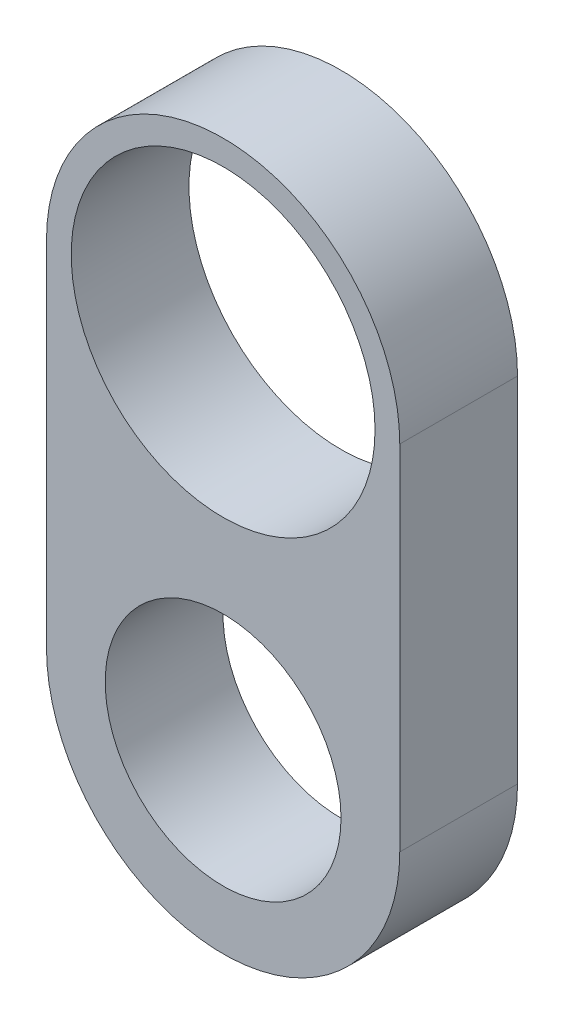
SolidWorks part; units mm, degrees
ref_plane "Front Plane" through (0, 0, 0) normal (0, 0, 1) x (1, 0, 0)
ref_plane "Top Plane" through (0, 0, 0) normal (0, 1, 0) x (1, 0, 0)
ref_plane "Right Plane" through (0, 0, 0) normal (1, 0, 0) x (0, 0, -1)
sketch "Sketch1" plane through (0, 0, 0) normal (0, 0, 1) x (1, 0, 0)
  line L0 (0, 0) -> (0, 38.1) construction
  line L1 (-19.05, 0) -> (-19.05, 38.1)
  line L2 (19.05, 0) -> (19.05, 38.1)
  arc A0 (-19.05, 0) -> (19.05, 0) centre (0, 0) ccw
  arc A1 (19.05, 38.1) -> (-19.05, 38.1) centre (0, 38.1) ccw
  point P3 (0, 19.05)
  point P8 (0, 57.15)
  point P9 (0, -19.05)
  dimension "D1" = 76.2
  dimension "D2" = 38.1
extrude "Boss-Extrude1" add sketch "Sketch1" along normal blind 12.7
sketch "Sketch2" plane through (0, 0, 12.7) normal (0, 0, 1) x (1, 0, 0)
  circle A0 centre (0, 0) radius 12.7152
  dimension "D1" = 25.4305
extrude "Cut-Extrude1" cut sketch "Sketch2" against normal through all both and the other way through all
sketch "Sketch3" plane through (0, 0, 12.7) normal (0, 0, 1) x (1, 0, 0)
  circle A0 centre (0, 38.1) radius 16.383
  dimension "D1" = 32.766
extrude "Cut-Extrude2" cut sketch "Sketch3" against normal through all both and the other way through all
equation "\"Da\" = 1.29'Diameter of the hole for feature A [in]"
equation "\"Ds\"= 1.0012'Diameter for the shaft[in]"
equation "\"L\"= 3'Length of feature[in]"
equation "\"W\"= 1.5'Width of link [in]"
equation "\"t\"= .5'Thickness of link [in]"
equation "\"D1@Sketch1\"=\"L\""
equation "\"D2@Sketch1\"=\"W\""
equation "\"D1@Boss-Extrude1\"=\"t\""
equation "\"D1@Sketch2\"=\"Ds\""
equation "\"D1@Sketch3\"=\"Da\""
